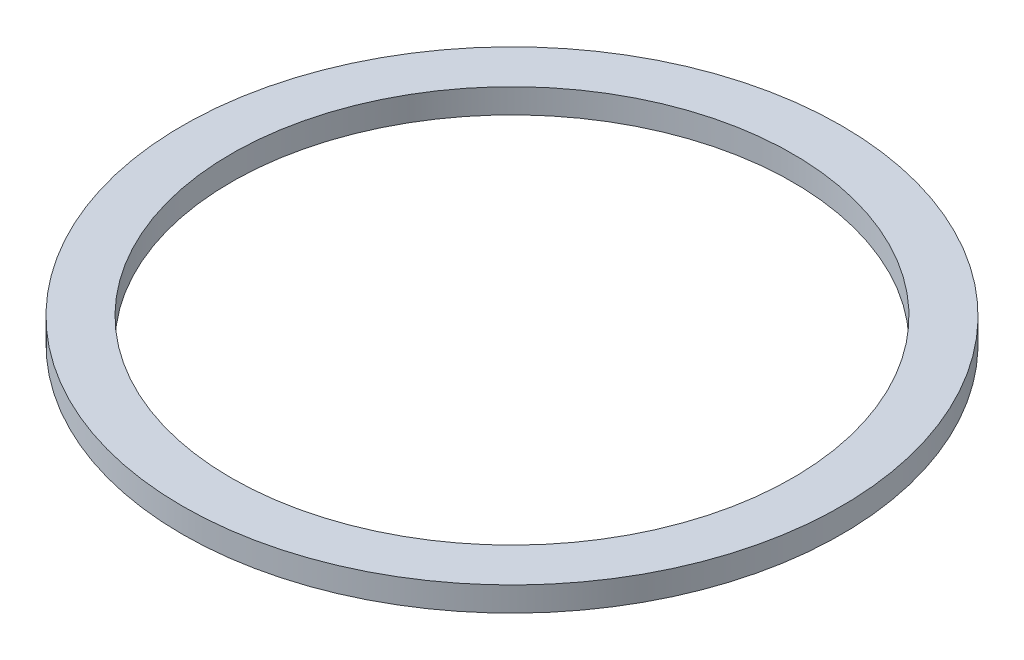
SolidWorks part; units mm, degrees
material "Glass"
ref_plane "Front Plane" through (0, 0, 0) normal (0, 0, 1) x (1, 0, 0)
ref_plane "Top Plane" through (0, 0, 0) normal (0, 1, 0) x (1, 0, 0)
ref_plane "Right Plane" through (0, 0, 0) normal (1, 0, 0) x (0, 0, -1)
sketch "Sketch1" plane through (0, 0, 0) normal (0, 1, 0) x (1, 0, 0)
  circle A0 centre (0, 0) radius 13.5
  circle A1 centre (0, 0) radius 11.5
  point P5 (0, 0)
  dimension "D1" = 27
  dimension "D2" = 2
extrude "Boss-Extrude1" add sketch "Sketch1" along normal blind 1
